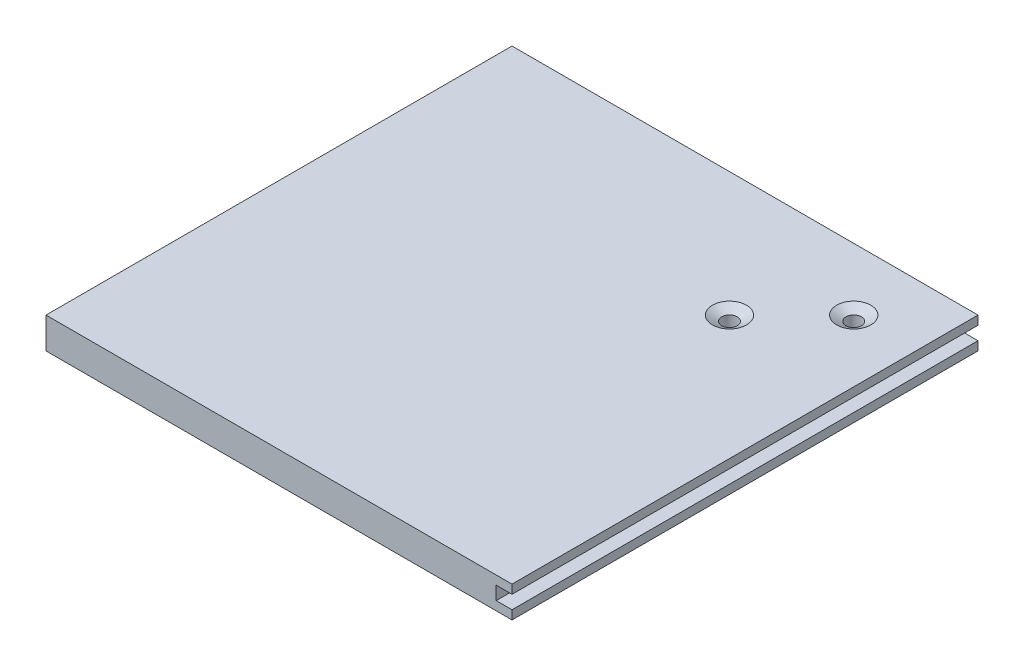
SolidWorks part; units mm, degrees
ref_plane "Front Plane" through (0, 0, 0) normal (0, 0, 1) x (1, 0, 0)
ref_plane "Top Plane" through (0, 0, 0) normal (0, 1, 0) x (1, 0, 0)
ref_plane "Right Plane" through (0, 0, 0) normal (1, 0, 0) x (0, 0, -1)
sketch "Sketch1" plane through (0, 0, 0) normal (0, 1, 0) x (1, 0, 0)
  line L0 (0, 0) -> (0, 150)
  line L1 (0, 0) -> (150, 0)
  line L2 (150, 0) -> (150, 150)
  line L3 (150, 150) -> (0, 150)
  dimension "D1" = 150
  dimension "D2" = 150
extrude "Boss-Extrude1" add sketch "Sketch1" along normal blind 10
sketch "Sketch2" plane through (0, 0, 0) normal (0, 0, 1) x (1, 0, 0)
  line L0 (150, 7.15) -> (144.9, 7.15)
  line L1 (150, 10) -> (150, 0) construction
  line L2 (144.9, 7.15) -> (144.9, 2.85)
  line L3 (144.9, 2.85) -> (150, 2.85)
  line L4 (150, 7.15) -> (150, 2.85)
  line L5 (0, 10) -> (150, 10) construction
  dimension "D1" = 4.3
  dimension "D2" = 2.85
  dimension "D3" = 5.1
extrude "Cut-Extrude1" cut sketch "Sketch2" against normal through all both and the other way through all
sketch "Sketch3" plane through (144.9, 0, 0) normal (1, 0, 0) x (0, 0, -1)
  line L5 (150, 2.85) -> (150, 7.15)
  line L6 (150, 7.15) -> (145, 7.15)
  line L7 (150, 7.15) -> (0, 7.15) construction
  line L8 (145, 7.15) -> (145, 2.85)
  line L9 (150, 2.85) -> (0, 2.85) construction
  line L10 (145, 2.85) -> (150, 2.85)
extrude "Cut-Extrude2" cut sketch "Sketch3" against normal through all both and the other way through all
sketch "Sketch4" plane through (0, 10, 0) normal (0, 1, 0) x (1, 0, 0)
  line L0 (150, 150) -> (0, 150) construction
  line L1 (150, 0) -> (150, 150) construction
  circle A0 centre (130, 130) radius 2.5
  circle A1 centre (110, 110) radius 2.5
  dimension "D3" = 5
  dimension "D5" = 40
  dimension "D6" = 5
  dimension "D1" = 20
  dimension "D2" = 20
  dimension "D4" = 40
extrude "Cut-Extrude3" cut sketch "Sketch4" against normal through all both and the other way through all
chamfer "Chamfer1" distance 3 angle 30 2 edges at (130, 10, -127.5) (110, 10, -107.5)
